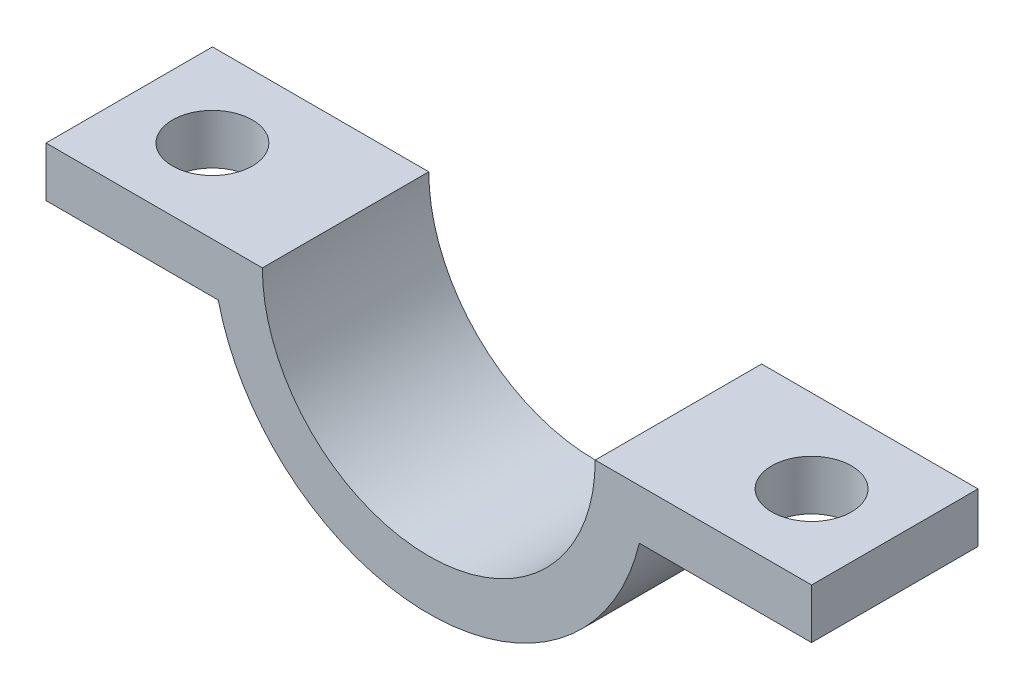
SolidWorks part; units mm, degrees
ref_plane "Front Plane" through (0, 0, 0) normal (0, 0, 1) x (1, 0, 0)
ref_plane "Top Plane" through (0, 0, 0) normal (0, 1, 0) x (1, 0, 0)
ref_plane "Right Plane" through (0, 0, 0) normal (1, 0, 0) x (0, 0, -1)
sketch "Sketch1" plane through (0, 0, 0) normal (0, 0, 1) x (1, 0, 0)
  line L0 (0, 0) -> (0, -8.856) construction
  line L1 (5, 0) -> (11.5, 0)
  line L2 (11.5, 0) -> (11.5, -1.5)
  line L3 (11.5, -1.5) -> (6.3246, -1.5)
  line L4 (-11.5, -1.5) -> (-6.3246, -1.5)
  line L5 (-11.5, 0) -> (-11.5, -1.5)
  line L6 (-5, 0) -> (-11.5, 0)
  arc A0 (-6.3246, -1.5) -> (6.3246, -1.5) centre (0, 0) ccw
  arc A1 (-5, 0) -> (5, 0) centre (0, 0) ccw
  point P3 (5.9546, -0.713)
  point P11 (5.198, 0)
  point P12 (5.9546, -1.7847)
  point P13 (5.7654, -1.7847)
  dimension "D1" = 5
  dimension "D2" = 6.5
  dimension "D3" = 1.5
  dimension "D4" = 11.5
extrude "Boss-Extrude1" add sketch "Sketch1" along normal mid plane 5
sketch "Sketch2" plane through (0, 0, 0) normal (0, 1, 0) x (1, 0, 0)
  line L0 (0, 0) -> (-11.5, 0) construction
  line L1 (-11.5, -2.5) -> (-11.5, 2.5) construction
  line L2 (0, 0) -> (0, 6.0321) construction
  circle A0 centre (-9, 0) radius 1.2
  circle A1 centre (9, 0) radius 1.2
  dimension "D1" = 2.4
  dimension "D2" = 2.5
extrude "Cut-Extrude1" cut sketch "Sketch2" against normal through all
